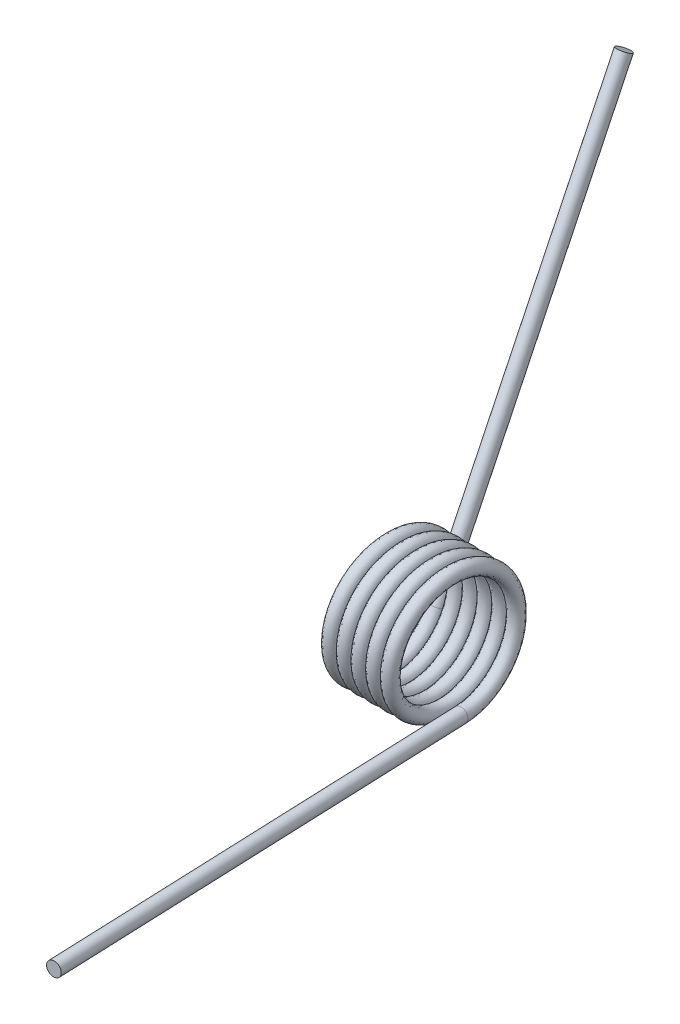
SolidWorks part; units mm, degrees
material "Plain Carbon Steel"
ref_plane "Front" through (0, 0, 0) normal (0, 0, 1) x (1, 0, 0)
ref_plane "Top" through (0, 0, 0) normal (0, 1, 0) x (1, 0, 0)
ref_plane "Right" through (0, 0, 0) normal (1, 0, 0) x (0, 0, -1)
sketch "Sketch1" plane through (0, 0, 0) normal (1, 0, 0) x (0, 0, -1)
  line L0 (0, 0) -> (0, -2.3495) construction
  line L1 (0, -2.3495) -> (0, -2.667) construction
  line L2 (0, -2.667) -> (0, -2.9845) construction
  line L3 (0, 2.9845) -> (0, -2.9845) construction
  circle A0 centre (0, 0) radius 2.3495 construction
  circle A1 centre (0, 0) radius 2.9845 construction
  circle A2 centre (0, 0) radius 2.667
  circle A3 centre (0, -2.667) radius 0.3175 construction
  circle A4 centre (0, 0) radius 1.778 construction
  dimension "Wire Dia" = 0.635
curve "Helix/Spiral1" pitch 0.6604 height 3.4143 turns 5.17
ref_plane "Plane1" through (0, -2.667, 0) normal (-0.0394, 0, -0.9992) x (0.9989, -0.024, -0.0394)
sketch "Sketch2" plane through (0, -2.667, 0) normal (-0.0394, 0, -0.9992) x (0.9989, -0.024, -0.0394)
  circle A0 centre (0, 0) radius 0.3175
  dimension "D1" = 0.635
sweep "Sweep1" add profiles "Sketch2" path "Helix/Spiral1"
sketch "Sketch3" plane through (0, 0, 0) normal (0.0394, 0, 0.9992) x (-0.9989, 0.024, 0.0394)
  circle A1 centre (-0.0639, 2.6662) radius 0.3175
  circle A2 centre (-0.0639, 2.6662) radius 0.3175
  dimension "D1" = 0
extrude "Extrude1" add sketch "Sketch3" along normal blind 19.05
sketch "Sketch4" plane through (-0.0053, 0.1177, -0.0647) normal (-0.0394, 0.8756, -0.4814) x (0.9992, 0.0342, -0.0195)
  circle A1 centre (-3.4099, 2.6692) radius 0.3175
  circle A2 centre (-3.4099, 2.6692) radius 0.3175
  dimension "D1" = 0
extrude "Extrude2" add sketch "Sketch4" along normal blind 19.05
sketch "Sketch5" plane through (0, 0, 0) normal (1, 0, 0) x (0, 0, -1)
  line L0 (-19.0352, -2.3495) -> (-19.0352, -2.9845) construction
  line L1 (-19.0352, -2.9845) -> (0, -2.9845) construction
  circle A0 centre (0, 0) radius 1.778 construction
  circle A1 centre (0, 0) radius 1.778
  ellipse E0 centre (-19.0352, -2.667) end of major axis (-19.0352, -2.9845) minor radius 0.0125 construction
equation "\"D4@Helix/Spiral1\"=\"Wire Dia@Sketch1\"+.001"
equation "\"D1@Sketch2\"=\"Wire Dia@Sketch1\""
equation "\"D1@Extrude2\"=\"Leg Length@Extrude1\""
